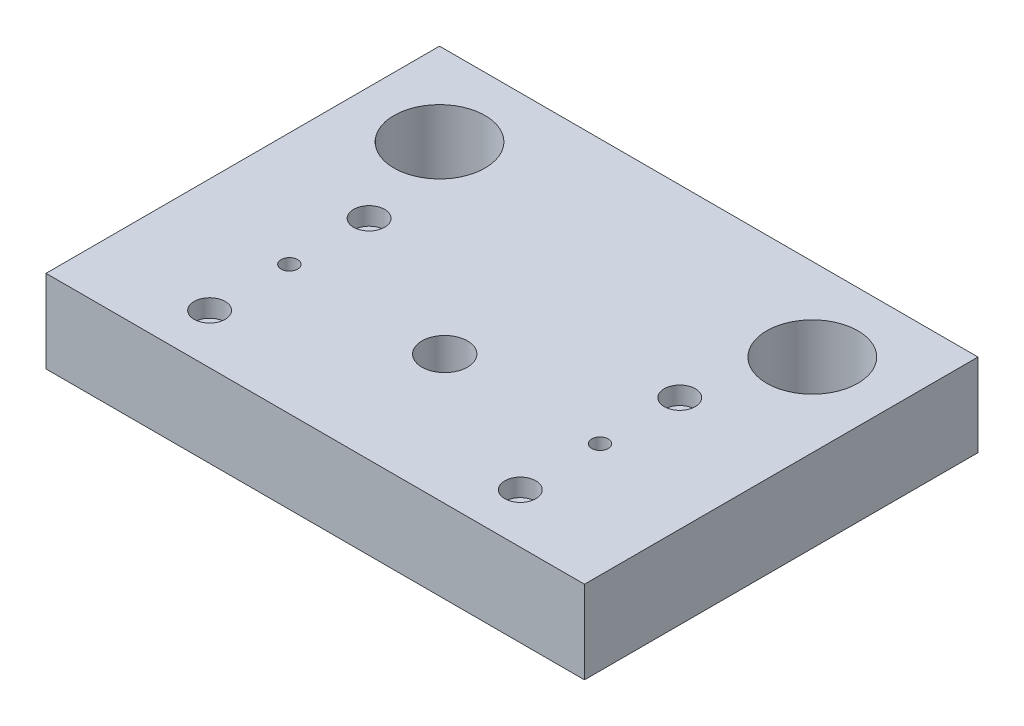
SolidWorks part; units mm, degrees
material "Plain Carbon Steel"
ref_plane "Front Plane" through (0, 0, 0) normal (0, 0, 1) x (1, 0, 0)
ref_plane "Top Plane" through (0, 0, 0) normal (0, 1, 0) x (1, 0, 0)
ref_plane "Right Plane" through (0, 0, 0) normal (1, 0, 0) x (0, 0, -1)
sketch "Sketch1" plane through (0, 0, 0) normal (0, 1, 0) x (1, 0, 0)
  line L0 (-130, 30) -> (130, 30) construction
  line L1 (-130, -95) -> (130, -95)
  line L2 (-130, -95) -> (-130, 95)
  line L3 (-130, 95) -> (130, 95)
  line L4 (130, -95) -> (130, 95)
  line L5 (-130, -95) -> (130, 95) construction
  line L6 (-130, 95) -> (130, -95) construction
  point P0 (0, 0)
  dimension "D1" = 260
  dimension "D2" = 190
  dimension "D3" = 125
extrude "Boss-Extrude1" add sketch "Sketch1" against normal blind 40
sketch "Sketch2" plane through (0, 0, 0) normal (0, 1, 0) x (1, 0, 0)
  line L0 (0, -95) -> (0, 95) construction
  line L1 (-130, -95) -> (130, -95) construction
  line L2 (130, 95) -> (-130, 95) construction
  circle A0 centre (-90, 55) radius 22
  circle A1 centre (90, 55) radius 22
  dimension "D2" = 44
  dimension "D1" = 180
  dimension "D3" = 150
extrude "Cut-Extrude1" cut sketch "Sketch2" against normal through all
ref_plane "Centre" through (0, 0, 32.5) normal (0, 0, 1) x (1, 0, 0)
hole_wizard "M24x2.0 Tapped Hole1" positions "Sketch5" profile "Sketch4" tap size "M24x2.0" standard "ISO" end condition through all
sketch "Sketch5" plane through (0, 0, 0) normal (0, 1, 0) x (1, 0, 0)
  line L0 (-22, -32.5) -> (22, -32.5) construction
  point P0 (0, -32.5)
sketch "Sketch4" plane through (0, 0, 32.5) normal (1, 0, 0) x (0, 0, 1)
  line L0 (0, 0) -> (0, 40)
  line L1 (0, 40) -> (11, 40)
  line L2 (11, 40) -> (11, 0)
  line L5 (11, 0) -> (0, 0)
  line L11 (0, -6.35) -> (0, 107.95) construction
  dimension "Thru Tap Drill Dia." = 22
  dimension "Thru Tap Drill Depth" = 40
cosmetic thread "Hole Thread1"
sketch "Sketch7" plane through (0, -40, 0) normal (0, 1, 0) x (1, 0, 0)
  line L0 (35.05, -4.95) -> (-35.05, -4.95) construction
  line L1 (35.05, -60.05) -> (35.05, -4.95) construction
  line L2 (-35.05, -60.05) -> (35.05, -60.05) construction
  line L3 (-35.05, -4.95) -> (-35.05, -60.05) construction
  line L4 (35.05, -4.95) -> (-35.05, -4.95)
  line L5 (35.05, -60.05) -> (35.05, -4.95)
  line L6 (-35.05, -60.05) -> (35.05, -60.05)
  line L7 (-35.05, -4.95) -> (-35.05, -60.05)
extrude "Cut-Extrude2" cut sketch "Sketch7" along normal blind 20
sketch "Sketch8" plane through (0, -40, 0) normal (0, -1, 0) x (1, 0, 0)
  circle A0 centre (-35.05, 60.05) radius 5
  circle A1 centre (35.05, 60.05) radius 5
  circle A2 centre (-35.05, 4.95) radius 5
  circle A3 centre (35.05, 4.95) radius 5
  dimension "D1" = 10
extrude "Cut-Extrude3" cut sketch "Sketch8" against normal up to surface (20 mm away) up to face at (0, -20, 32.5)
hole_wizard "CBORE for M8 Hex Socket Head Cap Screw1" positions "Sketch11" profile "Sketch10" counterbore size "M8" standard "ISO" end condition through all
sketch "Sketch11" plane through (0, 0, 0) normal (0, 1, 0) x (1, 0, 0)
  point P0 (-75, -71)
  point P3 (-75, 6)
  point P6 (75, 6)
  point P9 (75, -71)
sketch "Sketch10" plane through (-75, 0, 71) normal (1, 0, 0) x (0, 0, 1)
  line L0 (0, 0) -> (0, 40)
  line L1 (0, 40) -> (4.2, 40)
  line L3 (4.2, 40) -> (4.2, 8.6)
  line L4 (4.2, 8.6) -> (7.5, 8.6)
  line L5 (7.5, 8.6) -> (7.5, 0)
  line L7 (7.5, 0) -> (0, 0)
  line L11 (0, -6.35) -> (0, 107.95) construction
  dimension "Thru Hole Dia." = 8.4
  dimension "Thru Hole Depth" = 40
  dimension "C'Bore Dia." = 15
  dimension "C'Bore Depth" = 8.6
hole_wizard "Ø8.0mm Dowel Hole1" positions "Sketch14" profile "Sketch13" hole size "Ø8.0" standard "ISO" end condition through all
sketch "Sketch14" plane through (0, 0, 0) normal (0, 1, 0) x (1, 0, 0)
  point P0 (-75, -32.5)
  point P3 (75, -32.5)
sketch "Sketch13" plane through (-75, 0, 32.5) normal (1, 0, 0) x (0, 0, 1)
  line L0 (0, 0) -> (0, 40)
  line L1 (0, 40) -> (4, 40)
  line L2 (4, 40) -> (4, 0)
  line L5 (4, 0) -> (0, 0)
  line L11 (0, -6.35) -> (0, 107.95) construction
  dimension "Thru Hole Dia." = 8
  dimension "Thru Hole Depth" = 40
